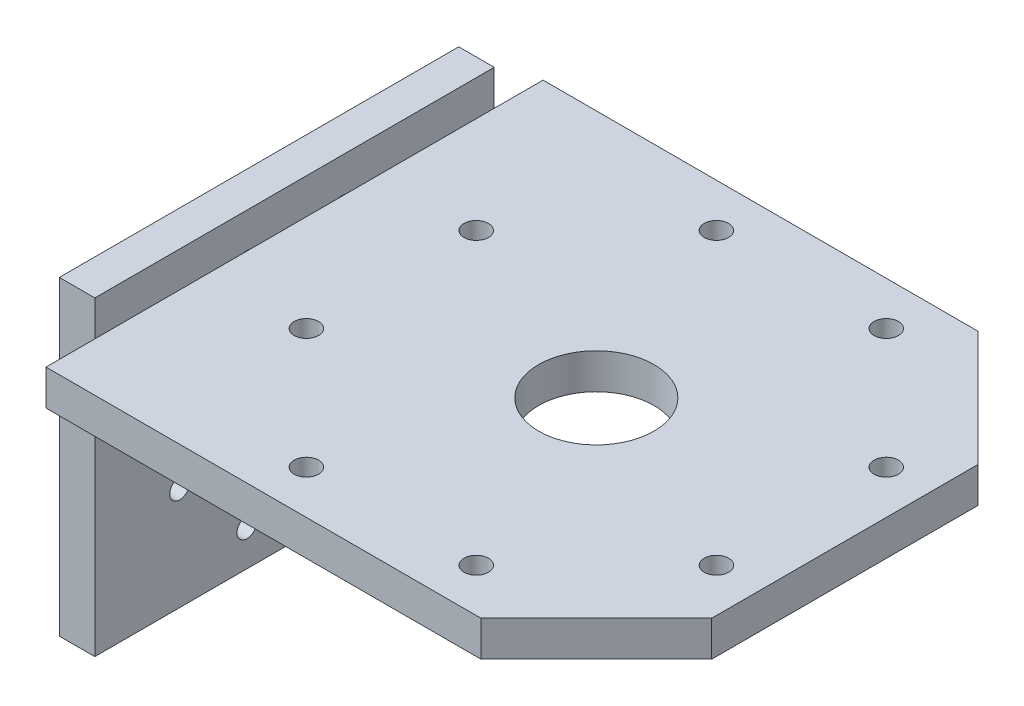
SolidWorks part; units mm, degrees
ref_plane "Front Plane" through (0, 0, 0) normal (0, 0, 1) x (1, 0, 0)
ref_plane "Top Plane" through (0, 0, 0) normal (0, 1, 0) x (1, 0, 0)
ref_plane "Right Plane" through (0, 0, 0) normal (1, 0, 0) x (0, 0, -1)
ref_plane "PL_Back_Plate_base" through (-76, 0, 0) normal (1, 0, 0) x (0, 0, -1)
sketch "SK_Back_Plate" plane through (-76, 0, 0) normal (1, 0, 0) x (0, 0, -1)
  line L0 (45, 36) -> (45, -34)
  line L1 (45, -34) -> (-45, -34)
  line L2 (-45, -34) -> (-45, 36)
  line L3 (-45, 36) -> (45, 36)
  circle A0 centre (25.8686, -10.7151) radius 2.25
  circle A1 centre (10.7151, -25.8686) radius 2.25
  circle A2 centre (-10.7151, -25.8686) radius 2.25
  circle A3 centre (-25.8686, -10.7151) radius 2.25
  circle A4 centre (-25.8686, 10.7151) radius 2.25
  circle A5 centre (-10.7151, 25.8686) radius 2.25
  circle A6 centre (10.7151, 25.8686) radius 2.25
  circle A7 centre (25.8686, 10.7151) radius 2.25
  circle A8 centre (0, 0) radius 6
  dimension "D9_SK_Back_Plate" = 4.5
  dimension "D12_SK_Back_Plate" = 4.5
  dimension "D15_SK_Back_Plate" = 4.5
  dimension "D18_SK_Back_Plate" = 4.5
  dimension "D21_SK_Back_Plate" = 4.5
  dimension "D24_SK_Back_Plate" = 4.5
  dimension "D27_SK_Back_Plate" = 4.5
  dimension "D30_SK_Back_Plate" = 4.5
  dimension "D33_SK_Back_Plate" = 12
  dimension "P1" = 45
  dimension "P2" = 36
  dimension "P3" = 45
  dimension "P4" = 34
  dimension "P5" = 45
  dimension "P6" = 34
  dimension "P7" = 45
  dimension "P8" = 36
  dimension "P10" = 25.8686
  dimension "P11" = 10.7151
  dimension "P13" = 10.7151
  dimension "P14" = 25.8686
  dimension "P16" = 10.7151
  dimension "P17" = 25.8686
  dimension "P19" = 25.8686
  dimension "P20" = 10.7151
  dimension "P22" = 25.8686
  dimension "P23" = 10.7151
  dimension "P25" = 10.7151
  dimension "P26" = 25.8686
  dimension "P28" = 10.7151
  dimension "P29" = 25.8686
  dimension "P31" = 25.8686
  dimension "P32" = 10.7151
extrude "Back_Plate" add sketch "SK_Back_Plate" along normal blind 8
ref_plane "PL_Roll_Pilot_Recess_base" through (-76, 0, 0) normal (1, 0, 0) x (0, 0, -1)
sketch "SK_Roll_Pilot_Recess" plane through (-76, 0, 0) normal (1, 0, 0) x (0, 0, -1)
  circle A0 centre (0, 0) radius 22.15
  dimension "D1_SK_Roll_Pilot_Recess" = 44.3
extrude "Roll_Pilot_Recess" cut sketch "SK_Roll_Pilot_Recess" along normal blind 2.2
ref_plane "PL_Medial_Plate_base" through (0, 20, 0) normal (0, 1, 0) x (1, 0, 0)
sketch "SK_Medial_Plate" plane through (0, 20, 0) normal (0, 1, 0) x (1, 0, 0)
  line L0 (-68, 56) -> (30, 56)
  line L1 (30, 56) -> (56, 30)
  line L2 (56, 30) -> (56, -30)
  line L3 (56, -30) -> (30, -56)
  line L4 (30, -56) -> (-68, -56)
  line L5 (-68, -56) -> (-68, 56)
  circle A0 centre (46.194, 19.1342) radius 2.75
  circle A1 centre (19.1342, 46.194) radius 2.75
  circle A2 centre (-19.1342, 46.194) radius 2.75
  circle A3 centre (-46.194, 19.1342) radius 2.75
  circle A4 centre (-46.194, -19.1342) radius 2.75
  circle A5 centre (-19.1342, -46.194) radius 2.75
  circle A6 centre (19.1342, -46.194) radius 2.75
  circle A7 centre (46.194, -19.1342) radius 2.75
  circle A8 centre (0, 0) radius 13
  dimension "D13_SK_Medial_Plate" = 5.5
  dimension "D16_SK_Medial_Plate" = 5.5
  dimension "D19_SK_Medial_Plate" = 5.5
  dimension "D22_SK_Medial_Plate" = 5.5
  dimension "D25_SK_Medial_Plate" = 5.5
  dimension "D28_SK_Medial_Plate" = 5.5
  dimension "D31_SK_Medial_Plate" = 5.5
  dimension "D34_SK_Medial_Plate" = 5.5
  dimension "D37_SK_Medial_Plate" = 26
  dimension "P1" = 68
  dimension "P2" = 56
  dimension "P3" = 30
  dimension "P4" = 56
  dimension "P5" = 56
  dimension "P6" = 30
  dimension "P7" = 56
  dimension "P8" = 30
  dimension "P9" = 30
  dimension "P10" = 56
  dimension "P11" = 68
  dimension "P12" = 56
  dimension "P14" = 46.194
  dimension "P15" = 19.1342
  dimension "P17" = 19.1342
  dimension "P18" = 46.194
  dimension "P20" = 19.1342
  dimension "P21" = 46.194
  dimension "P23" = 46.194
  dimension "P24" = 19.1342
  dimension "P26" = 46.194
  dimension "P27" = 19.1342
  dimension "P29" = 19.1342
  dimension "P30" = 46.194
  dimension "P32" = 19.1342
  dimension "P33" = 46.194
  dimension "P35" = 46.194
  dimension "P36" = 19.1342
extrude "Medial_Plate" add sketch "SK_Medial_Plate" along normal blind 8
equation "\"Roll_face_x\" = -76"
equation "\"Pitch_rear_y\" = -20"
